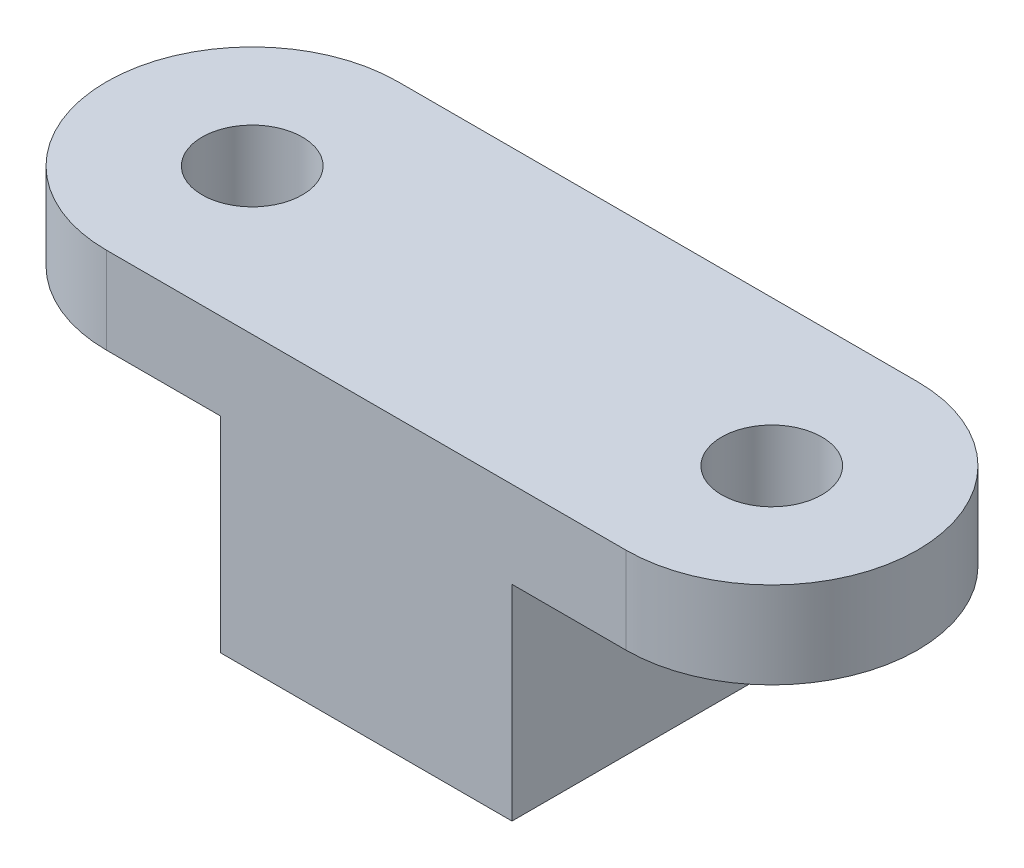
SolidWorks part; units mm, degrees
ref_plane "Front Plane" through (0, 0, 0) normal (0, 0, 1) x (1, 0, 0)
ref_plane "Top Plane" through (0, 0, 0) normal (0, 1, 0) x (1, 0, 0)
ref_plane "Right Plane" through (0, 0, 0) normal (1, 0, 0) x (0, 0, -1)
sketch "Sketch1" plane through (0, 0, 0) normal (0, 1, 0) x (1, 0, 0)
  line L0 (0, 0) -> (114, 0) construction
  line L2 (0, 32) -> (114, 32)
  line L3 (0, -32) -> (114, -32)
  arc A0 (0, 32) -> (0, -32) centre (0, 0) ccw
  arc A1 (114, -32) -> (114, 32) centre (114, 0) ccw
  circle A2 centre (0, 0) radius 11
  circle A3 centre (114, 0) radius 11
  point P5 (57, 0)
  dimension "D1" = 32
  dimension "D3" = 22
  dimension "D4" = 22
  dimension "D2" = 114
extrude "Boss-Extrude1" add sketch "Sketch1" along normal blind 19
sketch "Sketch2" plane through (0, 19, 0) normal (0, 1, 0) x (1, 0, 0)
  line L0 (57, 32) -> (57, -32) construction
  line L1 (114, 32) -> (0, 32) construction
  line L2 (0, -32) -> (114, -32) construction
  line L3 (-32, 0) -> (146, 0) construction
  arc A0 (0, 32) -> (0, -32) centre (0, 0) ccw construction
  arc A1 (114, -32) -> (114, 32) centre (114, 0) ccw construction
sketch "Sketch3" plane through (0, 0, 0) normal (0, -1, 0) x (1, 0, 0)
  line L0 (57, 32) -> (57, -32)
  line L1 (57, -32) -> (25, -32)
  line L2 (114, -32) -> (0, -32) construction
  line L3 (25, -32) -> (25, 32)
  line L4 (0, 32) -> (114, 32) construction
  line L5 (25, 32) -> (57, 32)
extrude "Boss-Extrude2" add sketch "Sketch3" along normal blind 45
sketch "Sketch4" plane through (57, 0, 0) normal (1, 0, 0) x (0, 0, -1)
  line L0 (32, -45) -> (-19, -45)
  line L1 (32, -45) -> (-32, -45) construction
  line L2 (-19, -45) -> (32, 6)
  line L3 (32, -45) -> (32, 0) construction
  line L4 (32, 6) -> (32, -45)
  dimension "D1" = 13
  dimension "D2" = 13
extrude "Cut-Extrude1" cut sketch "Sketch4" against normal blind 19
ref_plane "Plane1" through (57, 0, 0) normal (1, 0, 0) x (0, 0, -1)
mirror "Mirror1" about plane through (57, 0, 0) normal (1, 0, 0) of "Cut-Extrude1", "Boss-Extrude2"
